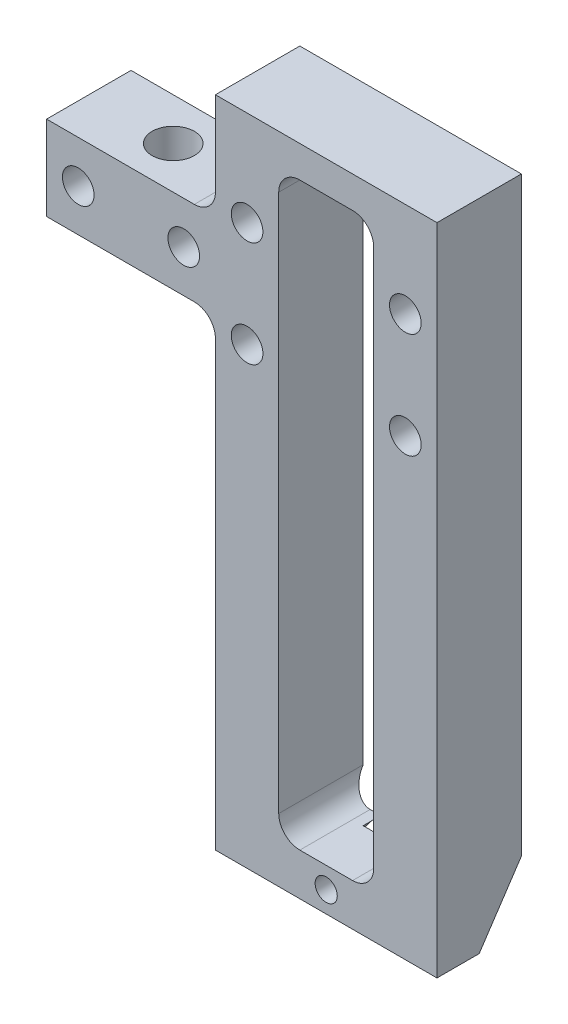
SolidWorks part; units mm, degrees
material "POM 乙缩醛共聚物"
ref_plane "前视基准面" through (0, 0, 0) normal (0, 0, 1) x (1, 0, 0)
ref_plane "上视基准面" through (0, 0, 0) normal (0, 1, 0) x (1, 0, 0)
ref_plane "右视基准面" through (0, 0, 0) normal (1, 0, 0) x (0, 0, -1)
sketch "草图1" plane through (0, 0, 0) normal (0, 0, 1) x (1, 0, 0)
  line L0 (0, 38.4307) -> (0, -35.9246) construction
  line L1 (-58.182, 0) -> (67.5873, 0) construction
  line L2 (0, 44) -> (0, 62) construction
  line L3 (0, 62) -> (37, 62) construction
  line L4 (37, 62) -> (37, 0)
  line L5 (37, 0) -> (16, 0)
  line L6 (16, 0) -> (16, 44)
  line L7 (16, 44) -> (0, 44)
  line L8 (0, 48) -> (20.2748, 48) construction
  line L9 (0, 52) -> (16, 52)
  line L10 (16, 52) -> (16, 62)
  line L11 (16, 62) -> (37, 62)
  line L12 (0, 52) -> (0, 44)
  circle A0 centre (19, 53) radius 1.5
  circle A1 centre (34, 53) radius 1.5
  circle A2 centre (19, 43) radius 1.5
  circle A3 centre (34, 43) radius 1.5
  circle A4 centre (3, 48) radius 1.5
  circle A5 centre (13, 48) radius 1.5
  dimension "D1" = 3
  dimension "D2" = 15
  dimension "D3" = 10
  dimension "D4" = 9
  dimension "D5" = 3
  dimension "D7" = 10
  dimension "D8" = 14
  dimension "D9" = 3
  dimension "D13" = 4
  dimension "D6" = 3
  dimension "D10" = 3
  dimension "D11" = 62
  dimension "D12" = 4
extrude "凸台-拉伸1" add sketch "草图1" along normal blind 8
fillet "圆角1" radius 2 2 edges at (16, 44, 4) (16, 52, 4)
sketch "草图2" plane through (0, 0, 8) normal (0, 0, 1) x (1, 0, 0)
  line L0 (26.5, 0) -> (26.5, 59) construction
  line L1 (16, 0) -> (37, 0) construction
  line L2 (37, 62) -> (16, 62) construction
  line L4 (22, 4) -> (31, 4)
  line L5 (22, 4) -> (22, 59)
  line L6 (22, 59) -> (31, 59)
  line L7 (31, 4) -> (31, 59)
  line L8 (22, 4) -> (31, 59) construction
  line L9 (22, 59) -> (31, 4) construction
  circle A0 centre (34, 43) radius 1.5 construction
  point P6 (26.5, 31.5)
  dimension "D2" = 3
  dimension "D1" = 3
  dimension "D3" = 4
extrude "切除-拉伸1" cut sketch "草图2" against normal through all
fillet "圆角2" radius 2 4 edges at (31, 4, 4) (22, 4, 4) (31, 59, 4) (22, 59, 4)
sketch "草图3" plane through (0, 44, 0) normal (0, -1, 0) x (1, 0, 0)
  line L0 (0, 4) -> (14, 4) construction
  line L1 (0, 8) -> (0, 0) construction
  line L2 (14, 0) -> (14, 8) construction
  circle A0 centre (8, 4) radius 2
  dimension "D1" = 4
  dimension "D2" = 8
extrude "切除-拉伸2" cut sketch "草图3" against normal through all
sketch "草图4" plane through (0, 0, 8) normal (0, 0, 1) x (1, 0, 0)
  line L0 (26.5, 0) -> (26.5, 62) construction
  line L1 (16, 0) -> (37, 0) construction
  line L2 (37, 62) -> (16, 62) construction
  circle A0 centre (26.5, 2) radius 1.05
  dimension "D1" = 2.1
  dimension "D2" = 2
extrude "切除-拉伸3" cut sketch "草图4" against normal through all
sketch "草图5" plane through (0, 0, 0) normal (0, 0, -1) x (-1, 0, 0)
  circle A0 centre (-26.5, 2) radius 2.5
  dimension "D1" = 5
extrude "切除-拉伸4" cut sketch "草图5" against normal blind 3
sketch "草图6" plane through (37, 0, 0) normal (1, 0, 0) x (0, 0, -1)
  line L0 (-4, 0) -> (0, 6)
  line L1 (-8, 0) -> (0, 0) construction
  line L2 (0, 6) -> (0, 0)
  line L3 (0, 0) -> (-4, 0)
extrude "切除-拉伸5" cut sketch "草图6" against normal blind 22
